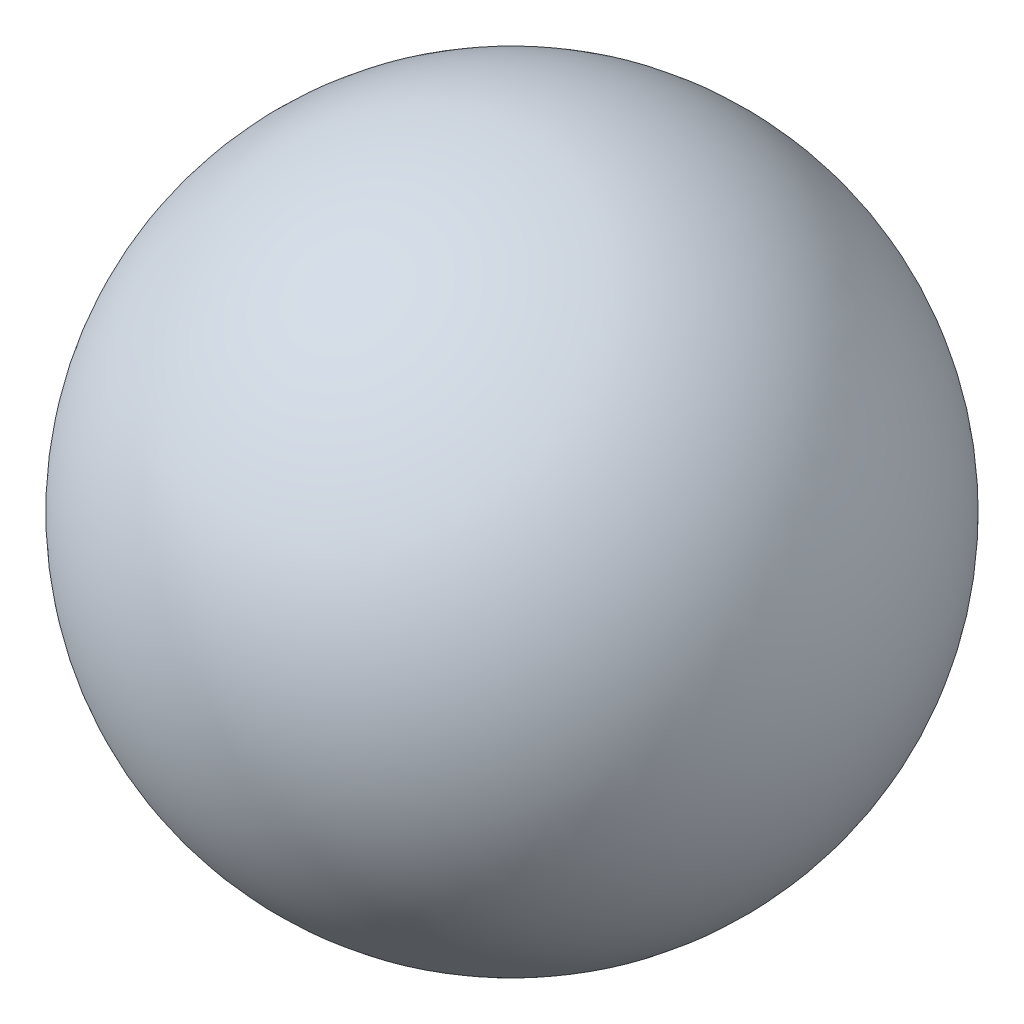
SolidWorks part; units mm, degrees
ref_plane "Plan de face" through (0, 0, 0) normal (0, 0, 1) x (1, 0, 0)
ref_plane "Plan de dessus" through (0, 0, 0) normal (0, 1, 0) x (1, 0, 0)
ref_plane "Plan de droite" through (0, 0, 0) normal (1, 0, 0) x (0, 0, -1)
sketch "Esquisse1" plane through (0, 0, 0) normal (0, 0, 1) x (1, 0, 0)
  line L0 (0, -25) -> (0, 25)
  arc A0 (0, 25) -> (0, -25) centre (0, 0) ccw
  point P4 (0, 0)
  dimension "D1" = 50
revolve "Révolution7" add sketch "Esquisse1" angle 360 about L0
sketch3d "Esquisse3D1"
  line L0 (0, -25, 0) -> (0, 25, 0)
  point P4 (0, 0, 0)
  dimension "D1" = 50
